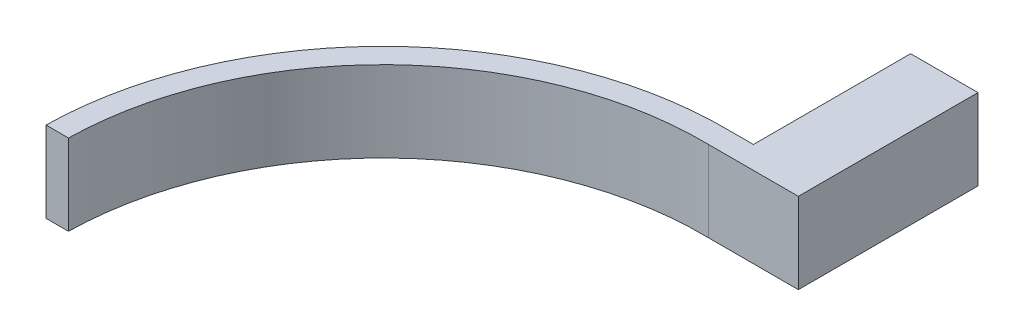
SolidWorks part; units mm, degrees
ref_plane "Front Plane" through (0, 0, 0) normal (0, 0, 1) x (1, 0, 0)
ref_plane "Top Plane" through (0, 0, 0) normal (0, 1, 0) x (1, 0, 0)
ref_plane "Right Plane" through (0, 0, 0) normal (1, 0, 0) x (0, 0, -1)
sketch "Sketch1" plane through (0, 0, 0) normal (0, 1, 0) x (1, 0, 0)
  line L0 (47.5, 30) -> (57.5, 30)
  line L1 (-35, -40) -> (-40, -40)
  line L2 (57.5, 30) -> (57.5, 70)
  line L3 (57.5, 70) -> (42.5, 70)
  line L10 (42.5, 70) -> (42.5, 35)
  line L12 (47.5, 30) -> (37.5, 30)
  line L13 (42.5, 35) -> (37.5, 35)
  arc A0 (-40, -40) -> (37.5, 35) centre (36.25, -41.25) cw
  arc A1 (-35, -40) -> (37.5, 30) centre (36.25, -41.25) cw
  point P0 (0, 0)
extrude "Boss-Extrude1" add sketch "Sketch1" along normal blind 18
sketch "Sketch4" plane through (0, 0, 0) normal (0, -1, 0) x (-1, 0, 0)
  line L0 (-50, 70) -> (-45, 70)
  line L1 (-57.5, 70) -> (-42.5, 70) construction
  line L2 (-50, 70) -> (-55, 70)
  line L3 (-45, 70) -> (-45, 40)
  line L4 (-45, 40) -> (-55, 40)
  line L5 (-55, 40) -> (-55, 70)
extrude "Cut-Extrude1" cut sketch "Sketch4" against normal blind 4
